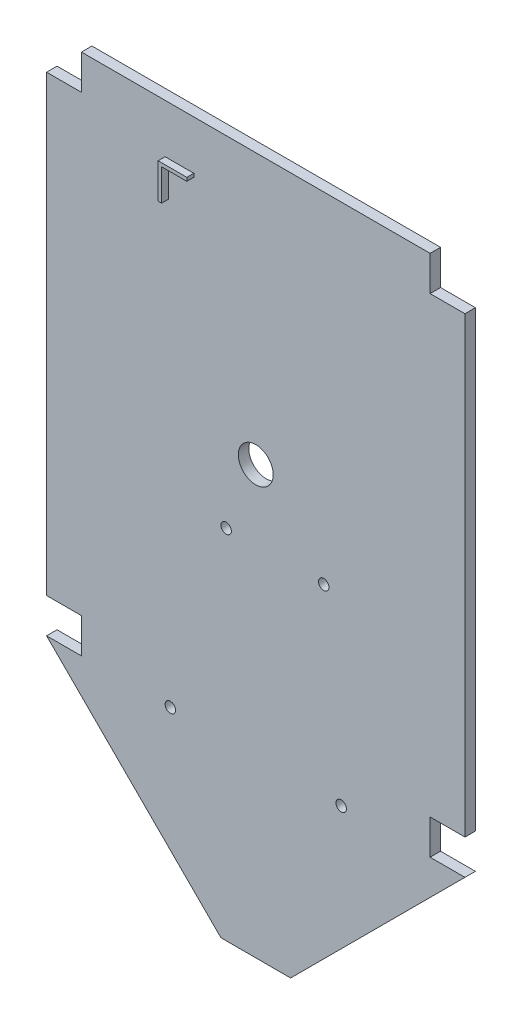
SolidWorks part; units mm, degrees
ref_plane "Plan de face" through (0, 0, 0) normal (0, 0, 1) x (1, 0, 0)
ref_plane "Plan de dessus" through (0, 0, 0) normal (0, 1, 0) x (1, 0, 0)
ref_plane "Plan de droite" through (0, 0, 0) normal (1, 0, 0) x (0, 0, -1)
sketch "Esquisse1" plane through (0, 0, 0) normal (0, 0, 1) x (1, 0, 0)
  line L0 (50, 0) -> (-50, 0)
  line L1 (-60, -10) -> (-60, -140)
  line L2 (-60, -150) -> (-50, -150)
  line L3 (-50, -150) -> (-50, -140)
  line L4 (-50, -140) -> (-60, -140)
  line L5 (-50, 0) -> (-50, -10)
  line L6 (-60, -150) -> (-10, -200)
  line L7 (0, 0) -> (0, -214.5143) construction
  line L8 (-50, -10) -> (-60, -10)
  line L9 (-10, -200) -> (10, -200)
  line L10 (50, -10) -> (60, -10)
  line L11 (60, -150) -> (10, -200)
  line L12 (50, 0) -> (50, -10)
  line L13 (50, -140) -> (60, -140)
  line L14 (50, -150) -> (50, -140)
  line L15 (60, -150) -> (50, -150)
  line L16 (60, -10) -> (60, -140)
  point P13 (0, -200)
  dimension "D1" = 50
  dimension "D2" = 10
  dimension "D3" = 10
  dimension "D4" = 10
  dimension "D5" = 10
  dimension "D6" = 10
  dimension "D7" = 150
  dimension "D8" = 45
  dimension "D9" = 10
extrude "Extrusion1" add sketch "Esquisse1" along normal blind 3
sketch "Esquisse2" plane through (0, 0, 3) normal (0, 0, 1) x (1, 0, 0)
  line L0 (-24.5, -150) -> (24.5, -150) construction
  line L1 (24.5, -150) -> (-24.5, -150) construction
  line L2 (24.5, -150) -> (24.5, -80.3554) construction
  line L3 (-8.5, -97.5) -> (19.5, -97.5) construction
  line L4 (0, -150) -> (0, -133.5348) construction
  line L5 (-60, -10) -> (-60, -140) construction
  line L8 (-10, -200) -> (10, -200) construction
  circle A0 centre (-24.5, -150) radius 1.5
  circle A1 centre (-8.5, -97.5) radius 1.5
  circle A2 centre (19.5, -97.5) radius 1.5
  circle A3 centre (24.5, -150) radius 1.5
  dimension "D1" = 3
  dimension "D2" = 3
  dimension "D3" = 3
  dimension "D4" = 3
  dimension "D5" = 49
  dimension "D6" = 52.5
  dimension "D7" = 28
  dimension "D8" = 5
  dimension "D9" = 60
  dimension "D10" = 50
extrude "Enlèv. mat.-Extru.1" cut sketch "Esquisse2" against normal blind 10
sketch "Esquisse3" plane through (0, 0, 3) normal (0, 0, 1) x (1, 0, 0)
  line L0 (-25, -15) -> (-25, -24.0375)
  line L1 (-25, -15) -> (-17.7738, -15)
  line L2 (-60, -10) -> (-60, -140) construction
  line L3 (50, 0) -> (-50, 0) construction
  line L4 (-17.7738, -15) -> (-17.7738, -14)
  line L5 (-17.7738, -14) -> (-26, -14)
  line L6 (-26, -14) -> (-26, -24.0375)
  line L7 (-26, -24.0375) -> (-25, -24.0375)
  dimension "D1" = 35
  dimension "D2" = 15
  dimension "D3" = 1
  dimension "D4" = 1
extrude "Extrusion2" add sketch "Esquisse3" along normal blind 2
sketch "Esquisse4" plane through (0, 0, 3) normal (0, 0, 1) x (1, 0, 0)
  line L0 (-60, -10) -> (-60, -140) construction
  circle A0 centre (0, -77.5) radius 5
  circle A1 centre (-8.5, -97.5) radius 1.5 construction
  dimension "D1" = 10
  dimension "D3" = 20
  dimension "D2" = 60
extrude "Enlèv. mat.-Extru.2" cut sketch "Esquisse4" against normal blind 52
